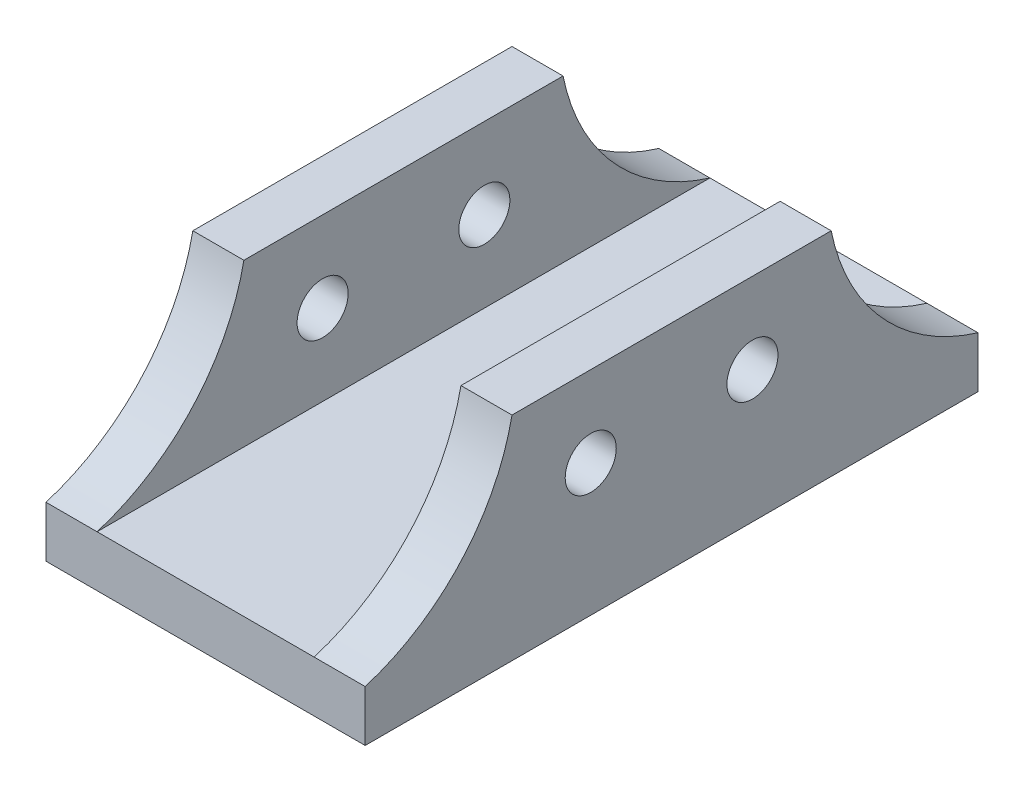
SolidWorks part; units mm, degrees
ref_plane "Front Plane" through (0, 0, 0) normal (0, 0, 1) x (1, 0, 0)
ref_plane "Top Plane" through (0, 0, 0) normal (0, 1, 0) x (1, 0, 0)
ref_plane "Right Plane" through (0, 0, 0) normal (1, 0, 0) x (0, 0, -1)
sketch "Sketch1" plane through (0, 0, 0) normal (1, 0, 0) x (0, 0, -1)
  line L0 (0, 0) -> (0, -52.9061) construction
  line L1 (-72, 0) -> (72, 0)
  line L2 (-72, 0) -> (-72, 50)
  line L3 (-72, 50) -> (72, 50)
  line L4 (72, 0) -> (72, 50)
  circle A0 centre (-19, 31) radius 6
  circle A1 centre (19, 31) radius 6
  dimension "D4" = 12
  dimension "D1" = 144
  dimension "D2" = 50
  dimension "D3" = 31
  dimension "D5" = 38
extrude "Boss-Extrude1" add sketch "Sketch1" along normal mid plane 75
sketch "Sketch2" plane through (0, 0, 72) normal (0, 0, 1) x (1, 0, 0)
  line L0 (37.5, 50) -> (-37.5, 50) construction
  line L1 (37.5, 50) -> (37.5, 0) construction
  line L2 (-25.5, 50) -> (25.5, 50)
  line L3 (-25.5, 50) -> (-25.5, 12)
  line L4 (-25.5, 12) -> (25.5, 12)
  line L5 (25.5, 50) -> (25.5, 12)
  line L6 (37.5, 0) -> (-37.5, 0) construction
  line L7 (-37.5, 50) -> (-37.5, 0) construction
  dimension "D1" = 12
  dimension "D2" = 12
  dimension "D3" = 12
extrude "Cut-Extrude1" cut sketch "Sketch2" against normal through all
sketch "Sketch3" plane through (37.5, 0, 0) normal (1, 0, 0) x (0, 0, -1)
  line L0 (72, 0) -> (72, 50) construction
  line L1 (72, 50) -> (-72, 50) construction
  line L2 (72, 12) -> (72, 50)
  line L3 (72, 50) -> (37.5, 50)
  line L4 (-72, 0) -> (72, 0) construction
  line L5 (0, 27.5) -> (0, -27.5) construction
  line L6 (-72, 50) -> (-37.5, 50)
  line L7 (-72, 12) -> (-72, 50)
  arc A0 (37.5, 50) -> (72, 12) centre (86.5212, 59.8449) ccw
  arc A1 (-37.5, 50) -> (-72, 12) centre (-86.5212, 59.8449) cw
  dimension "D2" = 50
  dimension "D1" = 12
  dimension "D3" = 75
extrude "Cut-Extrude2" cut sketch "Sketch3" against normal through all
